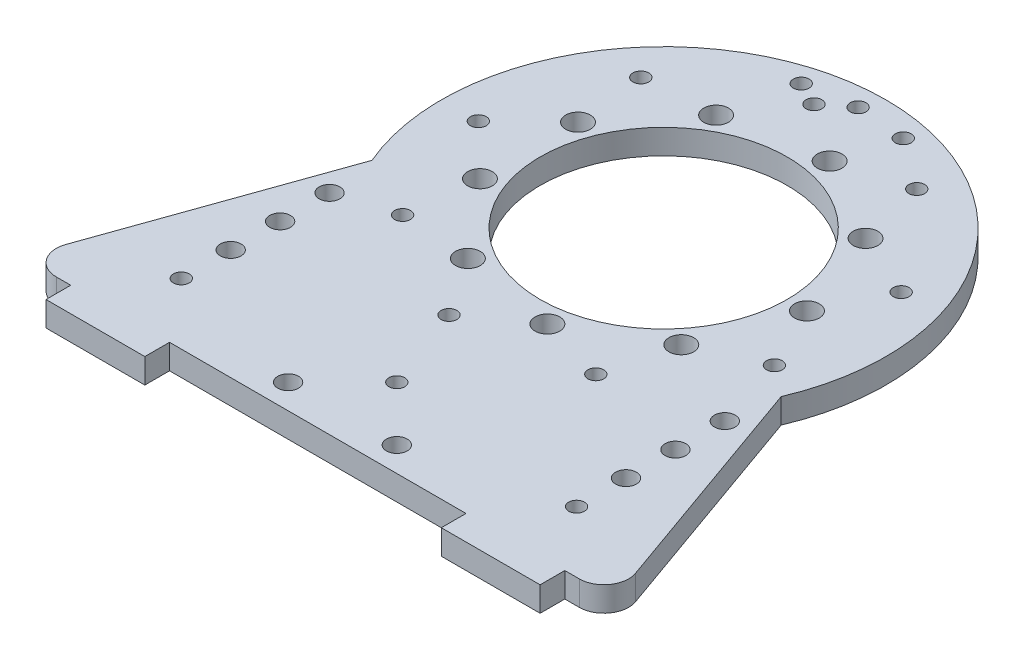
SolidWorks part; units mm, degrees
ref_plane "前视基准面" through (0, 0, 0) normal (0, 0, 1) x (1, 0, 0)
ref_plane "上视基准面" through (0, 0, 0) normal (0, 1, 0) x (1, 0, 0)
ref_plane "右视基准面" through (0, 0, 0) normal (1, 0, 0) x (0, 0, -1)
sketch "草图1" plane through (0, 0, 0) normal (0, 1, 0) x (1, 0, 0)
  line L0 (-60, 0) -> (-60, -70)
  line L1 (-60, -70) -> (60, -70)
  line L2 (60, -70) -> (60, 0)
  line L3 (0, 0) -> (0, 50000) construction
  arc A0 (60, 0) -> (0, 60) centre (0, 0) ccw
  circle A1 centre (0, 0) radius 25
  circle A11 centre (-40, -57.62) radius 1.6
  circle A12 centre (40, -57.62) radius 1.6
  arc A13 (0, 60) -> (-60, 0) centre (0, 0) ccw
  circle A16 centre (0, 0) radius 37.5 construction
  circle A17 centre (-37.5, 0) radius 1.6
  circle A25 centre (-28.7267, 24.1045) radius 1.6
  circle A26 centre (-6.5118, 36.9303) radius 1.6
  circle A28 centre (18.75, 32.476) radius 1.6
  circle A29 centre (35.2385, 12.8258) radius 1.6
  circle A30 centre (35.2385, -12.8258) radius 1.6
  circle A31 centre (18.75, -32.476) radius 1.6
  circle A32 centre (-6.5118, -36.9303) radius 1.6
  circle A33 centre (-28.7267, -24.1045) radius 1.6
  circle A34 centre (-11, -65) radius 2.1
  circle A36 centre (11, -65) radius 2.1
  circle A37 centre (0, -54) radius 1.6
  circle A38 centre (8.4882, 40) radius 1.6
  circle A39 centre (-1.5118, 40.8627) radius 1.6
  circle A40 centre (-11.4207, 39.2634) radius 1.6
  point P27 (0, 0)
  point P35 (0, 0)
  point P36 (0, 0)
  point P37 (-1.4605, 40.8646)
  point P43 (0, 0)
  point P46 (0, 0)
  point P51 (0, 0)
  point P52 (-2.9912, 40.7811)
  dimension "D1" = 120
  dimension "D3" = 50
  dimension "D4" = 9
  dimension "D5" = 11
  dimension "D6" = 75
  dimension "D7" = 3.2
  dimension "D11" = 3.2
  dimension "D14" = 16
  dimension "D12" = 4.2
  dimension "D13" = 3.2
  dimension "D15" = 3.2
  dimension "D16" = 40
  dimension "D2" = 70
  dimension "D9" = 80
  dimension "D10" = 12.38
  dimension "D8" = 5
  dimension "D17" = 15
  dimension "D19" = 10
  dimension "D18" = 3
extrude "凸台-拉伸1" add sketch "草图1" along normal mid plane 5
sketch "草图3" plane through (0, 2.5, 0) normal (0, 1, 0) x (1, 0, 0)
  line L0 (-28.7267, 24.1045) -> (-27.2511, 9.9186)
  line L1 (-27.2511, 9.9186) -> (-37.5, 0)
  circle A0 centre (-27.2511, 9.9186) radius 2.5
  circle A1 centre (-14.5, 25.1147) radius 2.5
  circle A2 centre (5.0358, 28.5594) radius 2.5
  circle A3 centre (22.2153, 18.6408) radius 2.5
  circle A4 centre (29, 0) radius 2.5
  circle A5 centre (22.2153, -18.6408) radius 2.5
  circle A6 centre (5.0358, -28.5594) radius 2.5
  circle A7 centre (-14.5, -25.1147) radius 2.5
  circle A8 centre (-27.2511, -9.9186) radius 2.5
  point P26 (0, 0)
  dimension "D1" = 29
  dimension "D2" = 5
  dimension "D3" = 9
extrude "切除-拉伸1" cut sketch "草图3" against normal blind 10 contours A8 | A1 | A2 | A3 | A4 | A5 | A6 | A7 | A0
sketch "草图4" plane through (0, 2.5, 0) normal (0, 1, 0) x (1, 0, 0)
  line L0 (-40, -47.62) -> (-40, -57.62) construction
  line L1 (0, 0) -> (0, -70) construction
  line L2 (-60, -70) -> (60, -70) construction
  circle A0 centre (-40, -47.62) radius 2.1
  circle A2 centre (-40, -57.62) radius 1.6 construction
  circle A3 centre (-40, -37.62) radius 2.1
  circle A4 centre (-40, -27.62) radius 2.1
  circle A5 centre (40, -47.62) radius 2.1
  circle A6 centre (40, -37.62) radius 2.1
  circle A7 centre (40, -27.62) radius 2.1
  dimension "D1" = 4.2
  dimension "D2" = 10
  dimension "D3" = 3
  dimension "D4" = 10
extrude "切除-拉伸2" cut sketch "草图4" against normal blind 10
sketch "草图5" plane through (0, 0, 70) normal (0, 0, 1) x (1, 0, 0)
  line L0 (0, 2.5) -> (0, -2.5) construction
  line L1 (-60, 2.5) -> (60, 2.5) construction
  line L2 (-60, -2.5) -> (60, -2.5) construction
  line L3 (50, -2.5) -> (30, -2.5)
  line L4 (-50, 2.5) -> (-30, 2.5)
  line L5 (-50, 2.5) -> (-50, -2.5)
  line L6 (-50, -2.5) -> (-30, -2.5)
  line L7 (-30, 2.5) -> (-30, -2.5)
  line L8 (30, 2.5) -> (30, -2.5)
  line L9 (50, 2.5) -> (30, 2.5)
  line L10 (50, 2.5) -> (50, -2.5)
  dimension "D1" = 20
  dimension "D2" = 30
extrude "凸台-拉伸2" add sketch "草图5" along normal blind 5
sketch "草图7" plane through (0, 2.5, 0) normal (0, 1, 0) x (1, 0, 0)
  line L0 (-41.407, -17.62) -> (-60, -70)
  line L1 (41.407, -17.62) -> (60, -70)
  line L2 (60, -70) -> (60, 0)
  line L3 (-60, -70) -> (-60, 0)
  line L4 (60, -70) -> (60, 0) construction
  arc A0 (-41.407, -17.62) -> (41.407, -17.62) centre (0, 0) cw
  circle A2 centre (40, -27.62) radius 2.1 construction
  arc A3 (-60, 0) -> (60, 0) centre (0, 0) cw
  arc A4 (60, 0) -> (-60, 0) centre (0, 0) ccw construction
  dimension "D1" = 45
  dimension "D2" = 10
extrude "切除-拉伸3" cut sketch "草图7" against normal through all
fillet "圆角1" radius 5 2 edges at (60, 0, 70) (-60, 0, 70)
